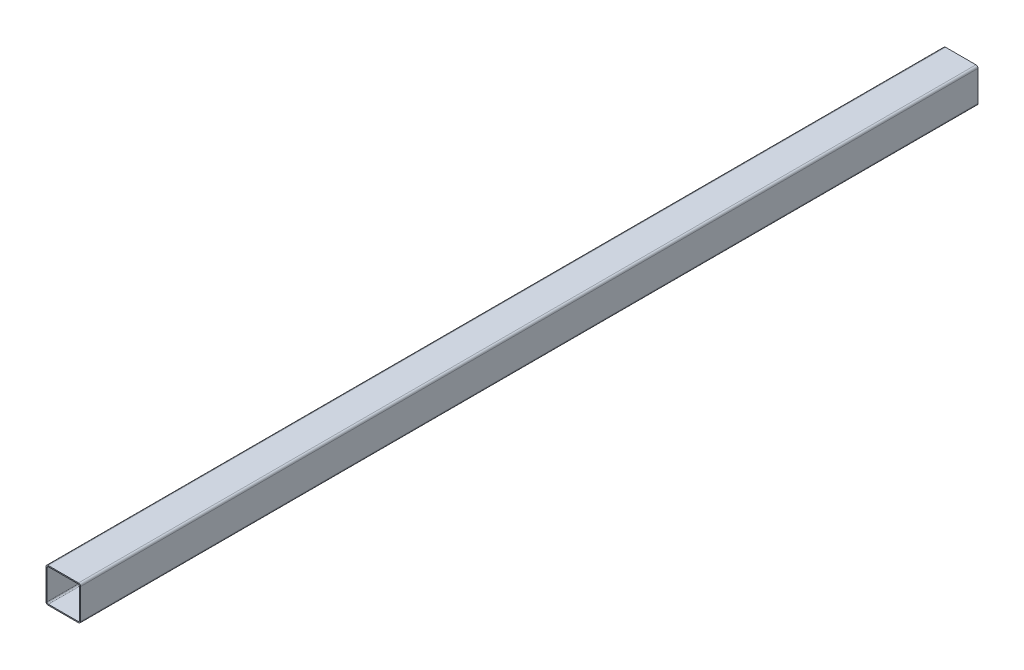
SolidWorks part; units mm, degrees
material "AISI 1020"
ref_plane "Спереди" through (0, 0, 0) normal (0, 0, 1) x (1, 0, 0)
ref_plane "Сверху" through (0, 0, 0) normal (0, 1, 0) x (1, 0, 0)
ref_plane "Справа" through (0, 0, 0) normal (1, 0, 0) x (0, 0, -1)
sketch "Эскиз1" plane through (0, 0, 0) normal (0, 0, 1) x (1, 0, 0)
  line B0 (-44, 50) -> (44, 50)
  line B1 (-50, 44) -> (-50, -44)
  line B2 (-44, -50) -> (44, -50)
  line B3 (50, 44) -> (50, -44)
  line B4 (-50, 50) -> (50, -50) construction
  line B5 (-50, -50) -> (50, 50) construction
  line B6 (-43, 47) -> (43, 47)
  line B7 (-47, 43) -> (-47, -43)
  line B8 (-43, -47) -> (43, -47)
  line B9 (47, 43) -> (47, -43)
  line B10 (-47, 47) -> (47, -47) construction
  line B11 (-47, -47) -> (47, 47) construction
  arc B12 (-50, -44) -> (-44, -50) centre (-44, -44) ccw
  arc B13 (44, -50) -> (50, -44) centre (44, -44) ccw
  arc B14 (44, 50) -> (50, 44) centre (44, 44) cw
  arc B15 (-44, 50) -> (-50, 44) centre (-44, 44) ccw
  arc B16 (-47, -43) -> (-43, -47) centre (-43, -43) ccw
  arc B17 (43, -47) -> (47, -43) centre (43, -43) ccw
  arc B18 (43, 47) -> (47, 43) centre (43, 43) cw
  arc B19 (-43, 47) -> (-47, 43) centre (-43, 43) ccw
sketch_block_instance "Блок1-1"
sketch_block "Блок1" parameters "D3"=6, "D4"=4, "D1"=100, "D2"=3
extrude "Бобышка-Вытянуть1" add sketch "Эскиз1" against normal blind 2600
